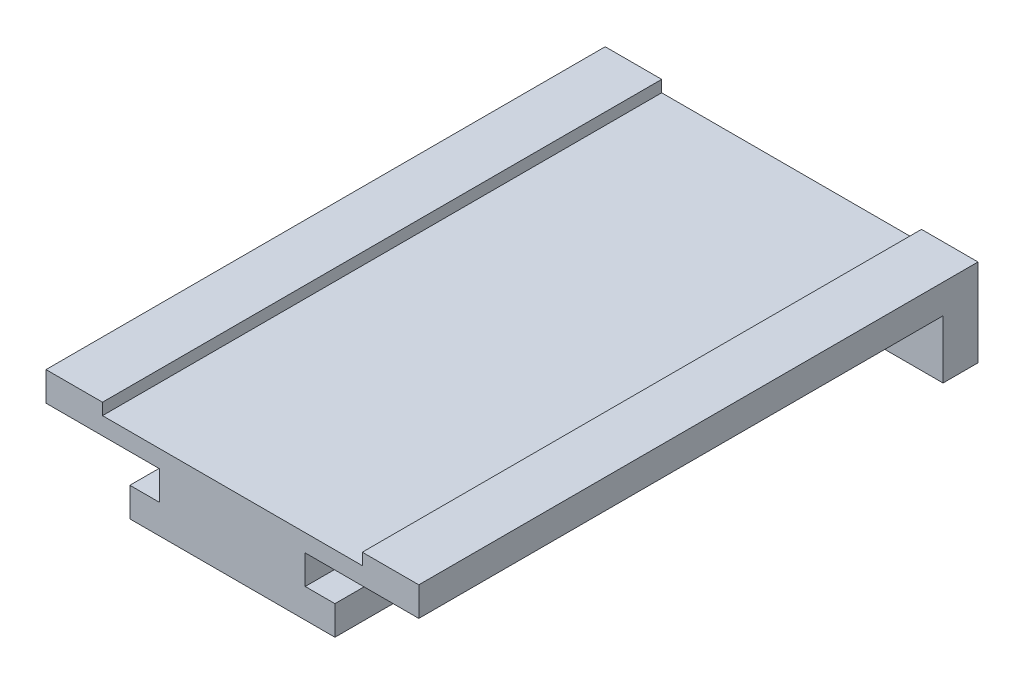
SolidWorks part; units mm, degrees
ref_plane "Front Plane" through (0, 0, 0) normal (0, 0, 1) x (1, 0, 0)
ref_plane "Top Plane" through (0, 0, 0) normal (0, 1, 0) x (1, 0, 0)
ref_plane "Right Plane" through (0, 0, 0) normal (1, 0, 0) x (0, 0, -1)
sketch "Sketch1" plane through (0, 0, 0) normal (0, 0, 1) x (1, 0, 0)
  line L1 (-3.2029, -2.2101) -> (5.5971, -2.2101)
  line L2 (-3.2029, -2.2101) -> (-3.2029, -4.7101)
  line L3 (-3.2029, -4.7101) -> (5.5971, -4.7101)
  line L4 (5.5971, -2.2101) -> (5.5971, -4.7101)
  line L5 (-3.2029, 0.2899) -> (3.0471, 0.2899)
  line L6 (-3.2029, 0.2899) -> (-3.2029, -2.2101)
  line L7 (-3.2029, -2.2101) -> (3.0471, -2.2101)
  line L8 (3.0471, 0.2899) -> (3.0471, -2.2101)
  line L13 (-3.2029, 0.2899) -> (12.7971, 0.2899)
  line L14 (-3.2029, 0.2899) -> (-3.2029, 2.7899)
  line L15 (-3.2029, 2.7899) -> (12.7971, 2.7899)
  line L16 (12.7971, 0.2899) -> (12.7971, 2.7899)
  dimension "D1" = 2.5
  dimension "D2" = 2.5
  dimension "D3" = 2.5
  dimension "D4" = 8.8
  dimension "D5" = 6.25
  dimension "D6" = 16
extrude "Boss-Extrude1" add sketch "Sketch1" along normal blind 45 contours L13 L16 L15 L14 L5 | L8 L5 L6 L1 | L4 L1 L2 L3
sketch "Sketch2" plane through (12.7971, 0, 0) normal (1, 0, 0) x (0, 0, -1)
  line L1 (-45, -4.7101) -> (-36.3578, -4.7101)
  line L2 (-45, -4.7101) -> (-45, -7.7101)
  line L3 (-45, -7.7101) -> (-36.3578, -7.7101)
  line L4 (-36.3578, -4.7101) -> (-36.3578, -7.7101)
  line L5 (-45, -7.7101) -> (-43, -7.7101)
  line L6 (-45, -7.7101) -> (-45, -14.7101)
  line L7 (-45, -14.7101) -> (-43, -14.7101)
  line L8 (-43, -7.7101) -> (-43, -14.7101)
  dimension "D1" = 3
  dimension "D2" = 7
  dimension "D3" = 2
mirror "Mirror1" about plane through (-3.2029, 0, 45) normal (-1, 0, 0) of "Boss-Extrude1"
sketch "Sketch8" plane through (0, -4.7101, 0) normal (0, -1, 0) x (1, 0, 0)
  line L0 (-3.2029, 45) -> (-3.2029, -0.3624) construction
  line L1 (-12.0029, 45) -> (5.5971, 45) construction
  line L2 (-19.2029, 45) -> (-19.2029, 0) construction
  line L3 (-19.2029, 22.5) -> (12.7971, 22.5) construction
  line L4 (12.7971, 45) -> (12.7971, 0) construction
  circle A0 centre (-3.2029, 32.5) radius 1.5
  circle A1 centre (-3.2029, 12.5) radius 1.5
  dimension "D1" = 10
extrude "Cut-Extrude2" cut sketch "Sketch8" against normal blind 3 draft 45
sketch "Sketch9" plane through (0, 0, 0) normal (0, 0, -1) x (-1, 0, 0)
  line L0 (12.0029, -4.7101) -> (-5.5971, -4.7101) construction
  line L1 (-12.7971, 2.7899) -> (19.2029, 2.7899)
  line L2 (-12.7971, 2.7899) -> (-12.7971, -4.7101)
  line L3 (-12.7971, -4.7101) -> (19.2029, -4.7101)
  line L4 (19.2029, 2.7899) -> (19.2029, -4.7101)
extrude "Boss-Extrude3" add sketch "Sketch9" along normal blind 3
sketch "Sketch10" plane through (0, 2.7899, 0) normal (0, 1, 0) x (1, 0, 0)
  line L0 (-3.2029, 3) -> (-3.2029, -45) construction
  line L1 (-19.2029, 3) -> (12.7971, 3) construction
  line L2 (-19.2029, -45) -> (12.7971, -45) construction
  line L3 (-14.3529, 3) -> (-14.3529, -45)
  line L4 (-14.3529, 3) -> (7.9471, 3)
  line L5 (-3.2029, 3) -> (-3.2029, -45)
  line L6 (-14.3529, -45) -> (7.9471, -45)
  line L7 (7.9471, 3) -> (7.9471, -45)
  line M7 (12.7971, 3) -> (-19.2029, 3)
  line M9 (-19.2029, -45) -> (12.7971, -45)
  dimension "D1" = 11.15
extrude "Cut-Extrude3" cut sketch "Sketch10" against normal blind 1 contours L5 L4 L3 M9 | L7 L5 M7 M9
